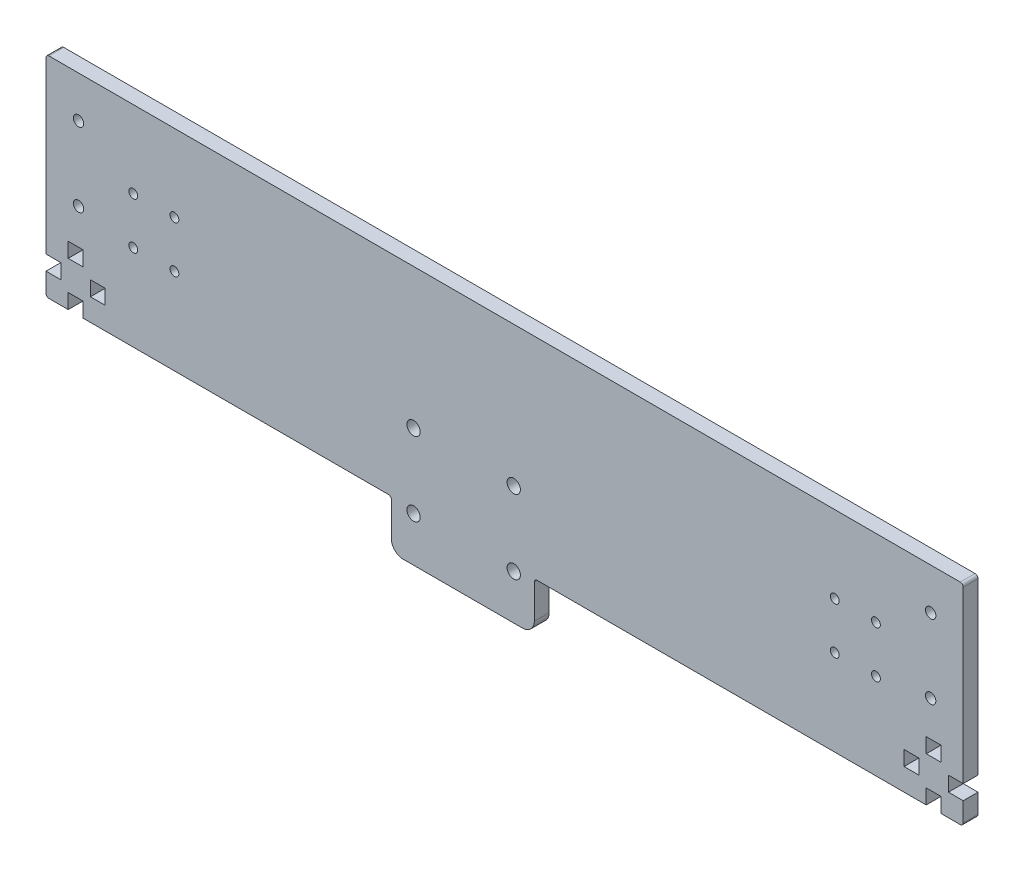
SolidWorks part; units mm, degrees
ref_plane "Front Plane" through (0, 0, 0) normal (0, 0, 1) x (1, 0, 0)
ref_plane "Top Plane" through (0, 0, 0) normal (0, 1, 0) x (1, 0, 0)
ref_plane "Right Plane" through (0, 0, 0) normal (1, 0, 0) x (0, 0, -1)
sketch "Sketch1" plane through (0, 0, 0) normal (0, 0, 1) x (1, 0, 0)
  line L0 (-10, -2.5019) -> (-10, -9.0019)
  line L1 (-2.5, 9.9981) -> (2.5, 9.9981)
  line L2 (-2.5, 9.9981) -> (-2.5, 4.9981)
  line L3 (-2.5, 4.9981) -> (2.5, 4.9981)
  line L4 (2.5, 9.9981) -> (2.5, 4.9981)
  line L5 (5, -2.5019) -> (10, -2.5019)
  line L6 (5, -2.5019) -> (5, 2.4981)
  line L7 (5, 2.4981) -> (10, 2.4981)
  line L8 (10, -2.5019) -> (10, 2.4981)
  line L9 (-10, 2.4981) -> (-5, 2.4981)
  line L11 (-10, -2.5019) -> (-5, -2.5019)
  line L12 (-5, 2.4981) -> (-5, -2.5019)
  line L14 (-2.5, -10.0019) -> (-2.5, -5.0019)
  line L15 (-2.5, -5.0019) -> (2.5, -5.0019)
  line L16 (2.5, -10.0019) -> (2.5, -5.0019)
  line L17 (106.724, -11.0019) -> (106.724, -22.4585)
  line L18 (-9, -10.0019) -> (-2.5, -10.0019)
  line L19 (-10, 60) -> (-10, 2.4981)
  line L20 (299, 61) -> (-9, 61)
  line L21 (300, -9.0019) -> (300, -2.5019)
  line L22 (156.0398, -10.0019) -> (287.5, -10.0019)
  line L23 (155.0398, -22.4585) -> (155.0398, -11.0019)
  line L24 (110.724, -26.4585) -> (151.0398, -26.4585)
  line L25 (2.5, -10.0019) -> (105.724, -10.0019)
  line L26 (145, 61) -> (145, 43.6071) construction
  line L27 (287.5, -10.0019) -> (287.5, -5.0019)
  line L28 (292.5, -5.0019) -> (287.5, -5.0019)
  line L29 (292.5, -10.0019) -> (292.5, -5.0019)
  line L30 (295, 2.4981) -> (295, -2.5019)
  line L31 (300, -2.5019) -> (295, -2.5019)
  line L32 (300, 2.4981) -> (295, 2.4981)
  line L33 (280, -2.5019) -> (280, 2.4981)
  line L34 (285, 2.4981) -> (280, 2.4981)
  line L35 (285, -2.5019) -> (285, 2.4981)
  line L36 (285, -2.5019) -> (280, -2.5019)
  line L37 (287.5, 9.9981) -> (287.5, 4.9981)
  line L38 (292.5, 4.9981) -> (287.5, 4.9981)
  line L39 (292.5, 9.9981) -> (292.5, 4.9981)
  line L40 (292.5, 9.9981) -> (287.5, 9.9981)
  line L41 (300, 2.4981) -> (300, 60)
  line L42 (292.5, -10.0019) -> (299, -10.0019)
  circle A2 centre (33.4, 34.9472) radius 1.5
  circle A4 centre (19.5, 34.9472) radius 1.5
  circle A6 centre (256.6, 34.9472) radius 1.5
  circle A8 centre (270.5, 34.9472) radius 1.5
  circle A10 centre (270.5, 19.1472) radius 1.5
  circle A12 centre (256.6, 19.1472) radius 1.5
  circle A14 centre (289, 22.0015) radius 1.75
  circle A16 centre (19.5, 19.1472) radius 1.5
  circle A18 centre (148.0828, 13.6839) radius 2.25
  circle A20 centre (148.0828, -11.3161) radius 2.25
  circle A22 centre (289, 47.0015) radius 1.75
  circle A32 centre (1, 22.0015) radius 1.75
  circle A34 centre (1, 47.0015) radius 1.75
  circle A36 centre (33.4, 19.1472) radius 1.5
  arc A38 (106.724, -11.0019) -> (105.724, -10.0019) centre (105.724, -11.0019) ccw
  arc A39 (-10, -9.0019) -> (-9, -10.0019) centre (-9, -9.0019) ccw
  arc A40 (-9, 61) -> (-10, 60) centre (-9, 60) ccw
  arc A41 (300, 60) -> (299, 61) centre (299, 60) ccw
  arc A42 (299, -10.0019) -> (300, -9.0019) centre (299, -9.0019) ccw
  arc A43 (156.0398, -10.0019) -> (155.0398, -11.0019) centre (156.0398, -11.0019) ccw
  arc A44 (151.0398, -26.4585) -> (155.0398, -22.4585) centre (151.0398, -22.4585) ccw
  arc A45 (106.724, -22.4585) -> (110.724, -26.4585) centre (110.724, -22.4585) ccw
  circle A46 centre (114.2249, -11.3161) radius 2.25
  circle A48 centre (114.2249, 13.6839) radius 2.25
  point P31 (145, 61)
  point P33 (157.5148, 43.6071)
  dimension "D1" = 5
  dimension "D2" = 5
  dimension "D3" = 7.5
  dimension "D4" = 5
  dimension "D5" = 5
  dimension "D6" = 15
  dimension "D7" = 7.5
  dimension "D8" = 5
  dimension "D9" = 5
  dimension "D10" = 10
  dimension "D11" = 5
  dimension "D12" = 5
extrude "Boss-Extrude1" add sketch "Sketch1" along normal blind 5
